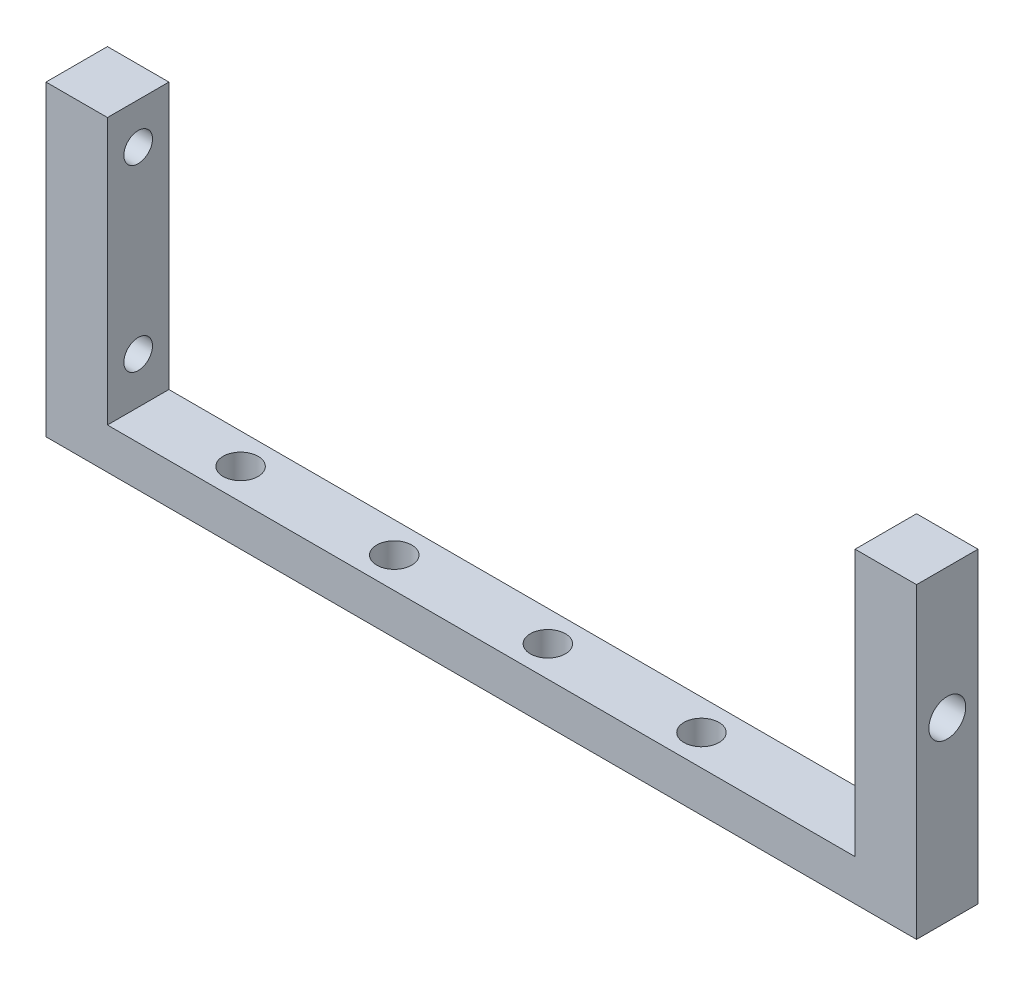
SolidWorks part; units mm, degrees
ref_plane "Front Plane" through (0, 0, 0) normal (0, 0, 1) x (1, 0, 0)
ref_plane "Top Plane" through (0, 0, 0) normal (0, 1, 0) x (1, 0, 0)
ref_plane "Right Plane" through (0, 0, 0) normal (1, 0, 0) x (0, 0, -1)
sketch "Sketch1" plane through (0, 0, 0) normal (0, 1, 0) x (1, 0, 0)
  line L1 (-107.95, -6.6449) -> (0, -6.6449)
  line L2 (-107.95, -6.6449) -> (-107.95, -14.2649)
  line L3 (-107.95, -14.2649) -> (0, -14.2649)
  line L4 (0, -6.6449) -> (0, -14.2649)
  dimension "D1" = 107.95
  dimension "D2" = 7.62
extrude "Boss-Extrude1" add sketch "Sketch1" along normal blind 5.08
sketch "Sketch2" plane through (0, 5.08, 0) normal (0, 1, 0) x (1, 0, 0)
  line L0 (0, -6.6449) -> (-107.95, -6.6449) construction
  line L1 (-107.95, -14.2649) -> (-100.33, -14.2649)
  line L2 (-107.95, -14.2649) -> (-107.95, -6.6449)
  line L3 (-107.95, -6.6449) -> (-100.33, -6.6449)
  line L4 (-100.33, -14.2649) -> (-100.33, -6.6449)
  line L6 (0, -14.2649) -> (-7.62, -14.2649)
  line L7 (0, -14.2649) -> (0, -6.6449)
  line L8 (0, -6.6449) -> (-7.62, -6.6449)
  line L9 (-7.62, -14.2649) -> (-7.62, -6.6449)
  dimension "D1" = 7.62
  dimension "D2" = 7.62
extrude "Boss-Extrude2" add sketch "Sketch2" along normal blind 33.02
sketch "Sketch3" plane through (-100.33, 0, 0) normal (1, 0, 0) x (0, 0, -1)
  line L0 (-6.6449, 38.1) -> (-6.6449, 5.08) construction
  line L1 (-14.2649, 38.1) -> (-6.6449, 38.1) construction
  circle A0 centre (-10.4549, 33.02) radius 1.778
  circle A1 centre (-10.4549, 10.795) radius 1.778
  dimension "D1" = 3.81
  dimension "D3" = 22.225
  dimension "D2" = 5.08
extrude "Cut-Extrude1" cut sketch "Sketch3" against normal blind 7.62
sketch "Sketch4" plane through (-7.62, 0, 0) normal (-1, 0, 0) x (0, 0, 1)
  line L0 (6.6449, 38.1) -> (14.2649, 38.1) construction
  line L1 (14.2649, 38.1) -> (14.2649, 5.08) construction
  circle A0 centre (10.4549, 21.9075) radius 2.286
  dimension "D1" = 16.1925
  dimension "D2" = 3.81
extrude "Cut-Extrude2" cut sketch "Sketch4" against normal blind 7.62
sketch "Sketch5" plane through (0, 5.08, 0) normal (0, 1, 0) x (1, 0, 0)
  line L0 (-100.33, -14.2649) -> (-100.33, -6.6449) construction
  line L1 (-100.33, -14.2649) -> (-7.62, -14.2649) construction
  circle A0 centre (-87.63, -10.4549) radius 2.1717
  circle A1 centre (-68.58, -10.4549) radius 2.1717
  circle A2 centre (-49.53, -10.4549) radius 2.1717
  circle A3 centre (-30.48, -10.4549) radius 2.1717
  dimension "D1" = 12.7
  dimension "D3" = 19.05
  dimension "D4" = 19.05
  dimension "D5" = 19.05
  dimension "D2" = 3.81
extrude "Cut-Extrude3" cut sketch "Sketch5" against normal blind 5.08
